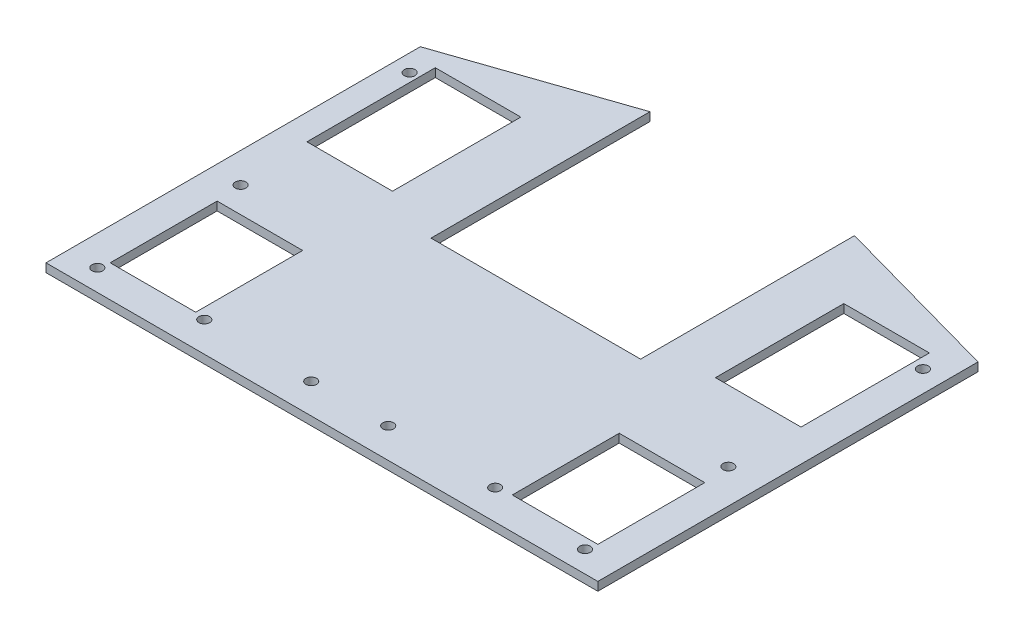
SolidWorks part; units mm, degrees
ref_plane "Front Plane" through (0, 0, 0) normal (0, 0, 1) x (1, 0, 0)
ref_plane "Top Plane" through (0, 0, 0) normal (0, 1, 0) x (1, 0, 0)
ref_plane "Right Plane" through (0, 0, 0) normal (1, 0, 0) x (0, 0, -1)
sketch "Sketch1" plane through (0, 0, 0) normal (0, 1, 0) x (1, 0, 0)
  line L0 (-48, 102.3684) -> (-48, 0)
  line L1 (-128, -100) -> (130, -100)
  line L2 (-128, -100) -> (-128, 75)
  line L4 (130, -100) -> (130, 77.7383)
  line L5 (-128, -100) -> (107.5142, 83.9955) construction
  line L6 (-106.8889, 82.2222) -> (130, -100) construction
  line L7 (-48, 0) -> (50, 0)
  line L8 (50, 0) -> (50, 100)
  line L10 (-128, 75) -> (-48, 102.3684)
  line L11 (75, -85) -> (115, -85)
  line L12 (75, -85) -> (75, -35)
  line L13 (75, -35) -> (115, -35)
  line L14 (115, -85) -> (115, -35)
  line L15 (75, 10) -> (115, 10)
  line L16 (75, 10) -> (75, 70)
  line L17 (75, 70) -> (115, 70)
  line L18 (115, 10) -> (115, 70)
  line L19 (-116, 10) -> (-76, 10)
  line L20 (-116, 10) -> (-116, 70)
  line L21 (-116, 70) -> (-76, 70)
  line L22 (-76, 10) -> (-76, 70)
  line L23 (-113, -85) -> (-73, -85)
  line L24 (-113, -85) -> (-113, -35)
  line L25 (-113, -35) -> (-73, -35)
  line L26 (-73, -85) -> (-73, -35)
  line L27 (130, 77.7383) -> (50, 100)
  line L28 (0, 145.2058) -> (0, -148.7313) construction
  circle A2 centre (-114, -90) radius 2.5
  circle A3 centre (-68, -86) radius 2.5
  circle A4 centre (-18, -86) radius 2.5
  circle A5 centre (-120, 62) radius 2.5
  circle A6 centre (-114, -23) radius 2.5
  circle A8 centre (18, -86) radius 2.5
  circle A9 centre (68, -86) radius 2.5
  circle A10 centre (114, -90) radius 2.5
  circle A11 centre (114, -23) radius 2.5
  circle A12 centre (120, 62) radius 2.5
  point P0 (0, 0)
  dimension "D23" = 5
  dimension "D24" = 5
  dimension "D25" = 5
  dimension "D32" = 5
  dimension "0.5" = 5
  dimension "D2" = 258
  dimension "D3" = 100
  dimension "D4" = 80
  dimension "D5" = 80
  dimension "D6" = 15
  dimension "D7" = 12
  dimension "D8" = 40
  dimension "D9" = 60
  dimension "D10" = 15
  dimension "D11" = 15
  dimension "D12" = 40
  dimension "D13" = 40
  dimension "D14" = 15
  dimension "D15" = 50
  dimension "D16" = 15
  dimension "D17" = 50
  dimension "D18" = 45
  dimension "D19" = 60
  dimension "D20" = 45
  dimension "D21" = 40
  dimension "D22" = 14
  dimension "D26" = 14
  dimension "D27" = 10
  dimension "D28" = 14
  dimension "D29" = 60
  dimension "D30" = 110
  dimension "D31" = 14
  dimension "D33" = 8
  dimension "D40" = 77
  dimension "D41" = 162
extrude "Boss-Extrude1" add sketch "Sketch1" along normal blind 4
